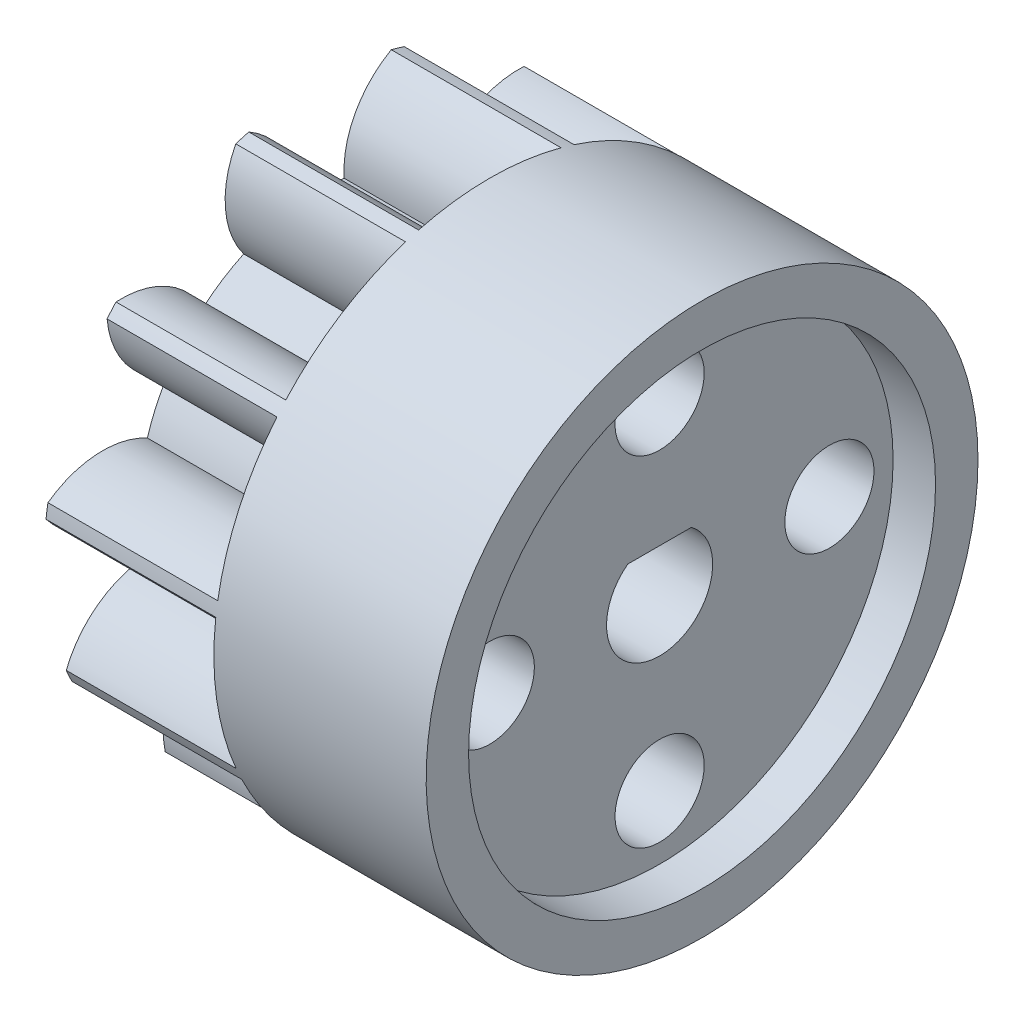
SolidWorks part; units mm, degrees
material "ABS"
ref_plane "Plane1" through (0, 0, 0) normal (0, 0, 1) x (1, 0, 0)
ref_plane "Plane2" through (0, 0, 0) normal (0, 1, 0) x (1, 0, 0)
ref_plane "Plane3" through (0, 0, 0) normal (1, 0, 0) x (0, 0, -1)
sketch "HoldingSke" plane through (0, 0, 0) normal (0, 1, 0) x (1, 0, 0)
  line L0 (0, 0) -> (0.4908, -0.0954)
  line L1 (-15, 0) -> (100, 0) construction
  line L2 (0, 0) -> (-2.1039, 2.3779)
  line L3 (0, 0) -> (-11.863, 4.5341)
  line L4 (0, 0) -> (8.4773, 1.6478)
  line L5 (0, 0) -> (-46.8476, -17.4728)
  line L6 (0, 0) -> (-6.6317, -4.4744)
  line L7 (-2.1039, 2.3779) -> (8.6586, 51.2059)
  line L8 (-76.2, 54.61) -> (-76.1, 54.61)
  line L9 (-71.009, 38.7566) -> (-53.1078, 45.2721)
  line L10 (-76.2, 71.12) -> (104.1128, 71.12)
  line L11 (0, 0) -> (-8, 0)
  line L12 (-76.2, 101.6) -> (-76.133, 101.6)
  line L13 (24.9733, 27.94) -> (52.9518, 28.4284)
  line L14 (24.9733, 27.94) -> (24.9743, 27.94)
  line L15 (24.9733, 27.94) -> (100.4006, 29.5858)
  line L16 (-63.627, -2) -> (-12.827, -2)
  circle A0 centre (0, 0) radius 0.4
  circle A1 centre (0, 0) radius 8.499
  circle A2 centre (0, 0) radius 37.5
  circle A3 centre (0, 0) radius 0.4
  dimension "MHD" = 16.998
  dimension "Hub_dia" = 75
  dimension "Bore" = 0.8
  dimension "MBD" = 0.8
  dimension "Num_teeth" = 11
  dimension "Pitch" = 0.5
  dimension "Overall_len" = 50
  dimension "Show_teeth" = 11
  dimension "Thickness" = 8
  dimension "OAL" = 50.0001
  dimension "T_dim" = 0.1
  dimension "Ap" = 20
  dimension "H" = 19.05
  dimension "Pitch_radius" = 180.3128
  dimension "Width" = 8
  dimension "Backlash" = 0.067
  dimension "Addendum_fac" = 1
  dimension "Dedendum_fac" = 1.25
  dimension "Clearance_fac" = 0.25
  dimension "Dedendum_add" = 0.001
  dimension "Module" = 2
sketch "BasProSke" plane through (0, 0, 0) normal (0, 1, 0) x (1, 0, 0)
  line L0 (-10, 0) -> (60, 0) construction
  line L1 (0, 0) -> (0, 13)
  line L2 (0, 0) -> (8, 0)
  line L3 (8, 0) -> (8, 13)
  line L4 (8, 13) -> (0, 13)
  dimension "Thickness" = 8
  dimension "Diameter" = 26
revolve "Base-Revolve" add sketch "BasProSke" angle 360 about L0
sketch "TooCutSke" plane through (0, 0, 0) normal (1, 0, 0) x (0, 0, -1)
  line L1 (0, 0) -> (0, 107) construction
  line L2 (0, 0) -> (-1.6825, 10.8706) construction
  line L3 (0, 0) -> (-6.1442, 20.9251) construction
  line L4 (-1.6825, 10.8706) -> (-3.0721, 10.4626) construction
  arc A0 (1.1399, 8.4222) -> (-1.1399, 8.4222) centre (0, 0) ccw
  arc A1 (3.3871, 12.5773) -> (-3.3871, 12.5773) centre (0, 0) ccw
  circle A2 centre (0, 0) radius 11 construction
  circle A3 centre (0, 0) radius 10.3366 construction
  arc A4 (-1.1399, 8.4222) -> (-3.3871, 12.5773) centre (-5.5288, 8.7337) ccw
  arc A5 (3.3871, 12.5773) -> (1.1399, 8.4222) centre (5.5288, 8.7337) ccw
  dimension "Root_dia" = 16.998
  dimension "Overcut_dia" = 26.0508
  dimension "Pitch_dia" = 22
  dimension "Base_dia" = 20.6732
  dimension "Flank_rad" = 4.4
  dimension "Half_ang" = 16.364
  dimension "Half_CT" = 1.4482
extrude "ToothCut" cut sketch "TooCutSke" along normal through all
fillet "Breaks" [suppressed] radius 0.04
fillet "RootFillets" [suppressed] radius 0.501
pattern_circular "TeethCuts" count 11 every 32.727 about axis through (-10, 0, 0) along (1, 0, 0) of "ToothCut", "RootFillets", "Breaks"
sketch "HubNeaOneSke" plane through (0, 0, 0) normal (-1, 0, 0) x (0, 0, 1)
  circle A0 centre (0, 0) radius 8.499
  dimension "Diameter" = 16.998
extrude "HubNearOne" [suppressed] add sketch "HubNeaOneSke" along normal blind 42.0001
sketch "HubNeaBotSke" plane through (0, 0, 0) normal (-1, 0, 0) x (0, 0, 1)
  circle A0 centre (0, 0) radius 8.499
  dimension "Diameter" = 16.998
extrude "HubNearBoth" [suppressed] add sketch "HubNeaBotSke" along normal blind 21
ref_plane "FarPln" through (8, 0, 0) normal (1, 0, 0) x (0, 0, -1)
sketch "HubFarSke" plane through (8, 0, 0) normal (1, 0, 0) x (0, 0, -1)
  circle A0 centre (0, 0) radius 8.499
  dimension "Diameter" = 16.998
extrude "HubFar" [suppressed] add sketch "HubFarSke" along normal blind 21
sketch "BorSke" plane through (0, 0, 0) normal (1, 0, 0) x (0, 0, -1)
  circle A0 centre (0, 0) radius 0.4
  dimension "Diameter" = 0.8
extrude "Bore" cut sketch "BorSke" along normal mid plane 100.0001
sketch "KeySke" plane through (0, 0, 0) normal (1, 0, 0) x (0, 0, -1)
  line L0 (-0.05, 0) -> (-0.05, 0.5)
  line L1 (-0.05, 0.5) -> (0.05, 0.5)
  line L2 (0.05, 0.5) -> (0.05, 0)
  line L3 (0, 0) -> (0, 34) construction
  line L4 (-0.05, 0) -> (0.05, 0)
  dimension "Offset" = 0.5
  dimension "Width" = 0.1
extrude "Keyway" [suppressed] cut sketch "KeySke" along normal mid plane 100.0001
pattern_circular "Keyway2" [suppressed] count 2 every 90 about axis through (-10, 0, 0) along (1, 0, 0)
sketch "Schizzo2" plane through (8, 0, 0) normal (1, 0, 0) x (0, 0, -1)
  circle A0 centre (0, 0) radius 13
  dimension "D1" = 26
extrude "Estrusione-Estrusione1" add sketch "Schizzo2" along normal blind 10
sketch "Schizzo1" plane through (18, 0, 0) normal (1, 0, 0) x (0, 0, -1)
  line L0 (-1.5, 2) -> (1.5, 2)
  arc A0 (-1.5, 2) -> (1.5, 2) centre (0, 0) ccw
  dimension "D1" = 5
  dimension "D2" = 2
extrude "Taglio-Estrusione1" cut sketch "Schizzo1" against normal blind 14
hole_wizard "Foro per Vite M3-1" positions "Schizzo3" profile "Schizzo4" hole size "M3" standard "DIN"
sketch "Schizzo3" plane through (18, 0, 0) normal (1, 0, 0) x (0, 0, -1)
  circle A0 centre (0, 0) radius 8 construction
  point P3 (0, 8)
  point P5 (8, 0)
  point P7 (0, -8)
  point P9 (-8, 0)
  dimension "D1" = 16
sketch "Schizzo4" plane through (18, 8, 0) normal (0, 1, 0) x (0, 0, -1)
  line L0 (0, 0) -> (0, 10.2618)
  line L1 (0, 10.2618) -> (2.1, 9)
  line L2 (2.1, 9) -> (2.1, 0)
  line L5 (2.1, 0) -> (0, 0)
  line L10 (0, 10.2618) -> (-2.1, 9) construction
  line L11 (0, -6.35) -> (0, 107.95) construction
  dimension "Hole Dia." = 4.2
  dimension "Hole Depth" = 9
  dimension "Drill Angle" = 118
sketch "Schizzo5" plane through (18, 0, 0) normal (1, 0, 0) x (0, 0, -1)
  circle A0 centre (0, 0) radius 11
  dimension "D1" = 22
extrude "Taglio-Estrusione2" cut sketch "Schizzo5" against normal blind 2
equation "' \"Module@HoldingSke\" = 6.35"
equation "' \"Num_teeth@HoldingSke\" = 12"
equation "' \"Ap@HoldingSke\" =  20"
equation "' \"Ap@HoldingSke\" = 20"
equation "' \"Width@HoldingSke\" = 0.5 * 25.4"
equation "' \"Hub_dia@HoldingSke\"= 1 * 25.4"
equation "' \"Hub_dia@HoldingSke\" = 1 * 25.4"
equation "' \"Overall_len@HoldingSke\" = 1.0 * 25.4"
equation "' \"Bore@HoldingSke\" = 0.75 * 25.4"
equation "' \"T_dim@HoldingSke\" = 0.1 * 25.4"
equation "' \"Width@KeySke\" = 0.25 * 25.4"
equation "' \"Show_teeth@HoldingSke\" = 13"
equation "' \"Backlash@HoldingSke\" = 0.009 * 25.4"
equation "' \"Addendum_fac@HoldingSke\" = 1.0"
equation "' \"Dedendum_fac@HoldingSke\" = 1.25"
equation "' \"Dedendum_add@HoldingSke\" = 0.00005 * 25.4"
equation "' \"Clearance_fac@HoldingSke\" = 0.25"
equation "\"Pitch@HoldingSke\" = 1 / \"Module@HoldingSke\""
equation "\"Overcut_dia@TooCutSke\" = (\"Num_teeth@HoldingSke\" + 2 * \"Addendum_fac@HoldingSke\") / \"Pitch@HoldingSke\" + 0.002 * 25.4"
equation "\"Pitch_dia@TooCutSke\" = \"Num_teeth@HoldingSke\" / \"Pitch@HoldingSke\""
equation "\"Base_dia@TooCutSke\" = \"Num_teeth@HoldingSke\" / \"Pitch@HoldingSke\" * cos((\"Ap@HoldingSke\"  * 3.14159265 / 180))"
equation "\"Root_dia@TooCutSke\" = (\"Num_teeth@HoldingSke\" + 2) / \"Pitch@HoldingSke\" - 2 * (\"Addendum_fac@HoldingSke\" + \"Dedendum_fac@HoldingSke\") / \"Pitch@HoldingSke\" - \"Dedendum_add@HoldingSke\" * 2"
equation "\"Half_ang@TooCutSke\" = 180 / \"Num_teeth@HoldingSke\""
equation "\"Half_CT@TooCutSke\" = \"Num_teeth@HoldingSke\" / \"Pitch@HoldingSke\" * sin((3.14159265 / 2 / \"Num_teeth@HoldingSke\")) / 2 - 7 * \"Backlash@HoldingSke\" / 4"
equation "\"Flank_rad@TooCutSke\" = \"Num_teeth@HoldingSke\" / \"Pitch@HoldingSke\" / 5"
equation "\"Radius@RootFillets\" = \"Clearance_fac@HoldingSke\" / \"Pitch@HoldingSke\" + \"Dedendum_add@HoldingSke\""
equation "\"Break_rad@Breaks\" = 0.02 / \"Pitch@HoldingSke\""
equation "\"Thickness@HoldingSke\" = \"Width@HoldingSke\""
equation "\"OAL@HoldingSke\" = \"Thickness@HoldingSke\""
equation "\"MHD@HoldingSke\" = (\"Num_teeth@HoldingSke\" + 2) / \"Pitch@HoldingSke\" - 2 * (\"Addendum_fac@HoldingSke\" + \"Dedendum_fac@HoldingSke\")  / \"Pitch@HoldingSke\" - \"Dedendum_add@HoldingSke\" * 2"
equation "\"MBD@HoldingSke\" = (\"Num_teeth@HoldingSke\" + 2) / \"Pitch@HoldingSke\" - 2 * (\"Addendum_fac@HoldingSke\" + \"Dedendum_fac@HoldingSke\")  / \"Pitch@HoldingSke\" - \"Dedendum_add@HoldingSke\" * 2 - 0.002 * 25.4"
equation "\"MHD@HoldingSke\" = ((sgn( \"MHD@HoldingSke\" - \"Hub_dia@HoldingSke\" )-1)*( \"MHD@HoldingSke\" - \"Hub_dia@HoldingSke\" ))/-2+ \"Hub_dia@HoldingSke\""
equation "\"MBD@HoldingSke\" = ((sgn( \"MBD@HoldingSke\" - \"Bore@HoldingSke\" )-1)*( \"MBD@HoldingSke\" - \"Bore@HoldingSke\" ))/-2+ \"Bore@HoldingSke\""
equation "\"OAL@HoldingSke\" = ((sgn( \"OAL@HoldingSke\" - \"Overall_len@HoldingSke\" )+1)*( \"OAL@HoldingSke\" - \"Overall_len@HoldingSke\" ))/2 + \"Overall_len@HoldingSke\" + 0.000002 * 25.4"
equation "\"Num_teeth@TeethCuts\" = int( \"Show_teeth@HoldingSke\" ) + 1"
equation "\"Num_teeth@TeethCuts\" = ((sgn( \"Num_teeth@TeethCuts\" - \"Num_teeth@HoldingSke\" )-1)*( \"Num_teeth@TeethCuts\" - \"Num_teeth@HoldingSke\" ))/-2+ \"Num_teeth@HoldingSke\""
equation "\"Num_teeth@TeethCuts\" = ((sgn( \"Num_teeth@TeethCuts\" - 2.0)+1)*( \"Num_teeth@TeethCuts\" - 2.0))/2 +2.0"
equation "\"Angle@TeethCuts\" = 360.0 / \"Num_teeth@HoldingSke\""
equation "\"Diameter@BasProSke\" = (\"Num_teeth@HoldingSke\" + 2 * \"Addendum_fac@HoldingSke\") / \"Pitch@HoldingSke\""
equation "\"Thickness@BasProSke\"  = \"Thickness@HoldingSke\""
equation "' \"Fillet_rad@BasProSke\" =  \"Thickness@HoldingSke\" * 0.05"
equation "' \"Fillet_rad@BasProSke\" = \"Thickness@HoldingSke\" * 0.05"
equation "\"MHD@HoldingSke\" = ((sgn( \"MHD@HoldingSke\" - \"Root_dia@TooCutSke\" )-1)*( \"MHD@HoldingSke\" - \"Root_dia@TooCutSke\" ))/-2+ \"Root_dia@TooCutSke\""
equation "\"Diameter@HubNeaOneSke\" = \"MHD@HoldingSke\""
equation "\"Length@HubNearOne\" = \"OAL@HoldingSke\" - \"Thickness@BasProSke\""
equation "\"Diameter@HubNeaBotSke\" = \"MHD@HoldingSke\""
equation "\"Length@HubNearBoth\" = ( \"OAL@HoldingSke\" - \"Thickness@BasProSke\" ) / 2.0"
equation "\"Thickness@FarPln\" = \"Thickness@BasProSke\""
equation "\"Diameter@HubFarSke\" = \"MHD@HoldingSke\""
equation "\"Length@HubFar\" = ( \"OAL@HoldingSke\" - \"Thickness@BasProSke\" ) / 2.0"
equation "\"Diameter@BorSke\" = \"MBD@HoldingSke\""
equation "\"D1@Bore\" = \"OAL@HoldingSke\" * 2.0"
equation "\"D1@Keyway\" = \"OAL@HoldingSke\" * 2.0"
equation "\"Offset@KeySke\" = \"T_dim@HoldingSke\" + \"MBD@HoldingSke\" / 2.0"
